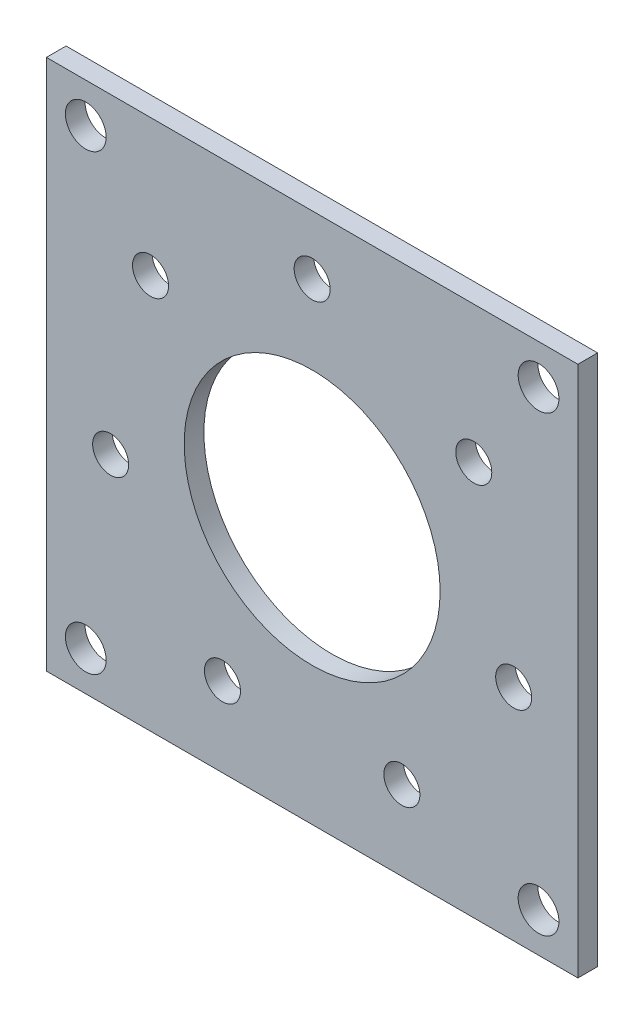
SolidWorks part; units mm, degrees
ref_plane "Plano frontal" through (0, 0, 0) normal (0, 0, 1) x (1, 0, 0)
ref_plane "Plano superior" through (0, 0, 0) normal (0, 1, 0) x (1, 0, 0)
ref_plane "Plano direito" through (0, 0, 0) normal (1, 0, 0) x (0, 0, -1)
sketch "Esboço1" plane through (0, 0, 0) normal (0, 0, 1) x (1, 0, 0)
  line L0 (-85.1606, 0) -> (82.682, 0) construction
  line L1 (-67.5, -67.5) -> (67.5, -67.5)
  line L2 (-67.5, -67.5) -> (-67.5, 67.5)
  line L3 (-67.5, 67.5) -> (67.5, 67.5)
  line L4 (67.5, -67.5) -> (67.5, 67.5)
  line L5 (-67.5, -67.5) -> (67.5, 67.5) construction
  line L6 (-67.5, 67.5) -> (67.5, -67.5) construction
  line L7 (0, 80.2153) -> (0, -99.5818) construction
  circle A0 centre (-57.5, 57.5) radius 5.1783
  circle A1 centre (-57.5, -57.5) radius 5.1783
  circle A2 centre (57.5, -57.5) radius 5.1783
  circle A3 centre (57.5, 57.5) radius 5.1783
  circle A4 centre (0, 0) radius 32.5
  circle A5 centre (0, 52.5) radius 4.577
  circle A6 centre (41.0462, 32.7332) radius 4.577
  circle A7 centre (51.1837, -11.6823) radius 4.577
  circle A8 centre (22.7789, -47.3009) radius 4.577
  circle A9 centre (-22.7789, -47.3009) radius 4.577
  circle A10 centre (-51.1837, -11.6823) radius 4.577
  circle A11 centre (-41.0462, 32.7332) radius 4.577
  point P0 (0, 0)
  point P37 (0, 0)
  dimension "D4" = 65
  dimension "D1" = 135
  dimension "D2" = 135
  dimension "D3" = 10
  dimension "D5" = 52.5
  dimension "D6" = 7
extrude "Ressalto-extrusão3" add sketch "Esboço1" along normal blind 5
